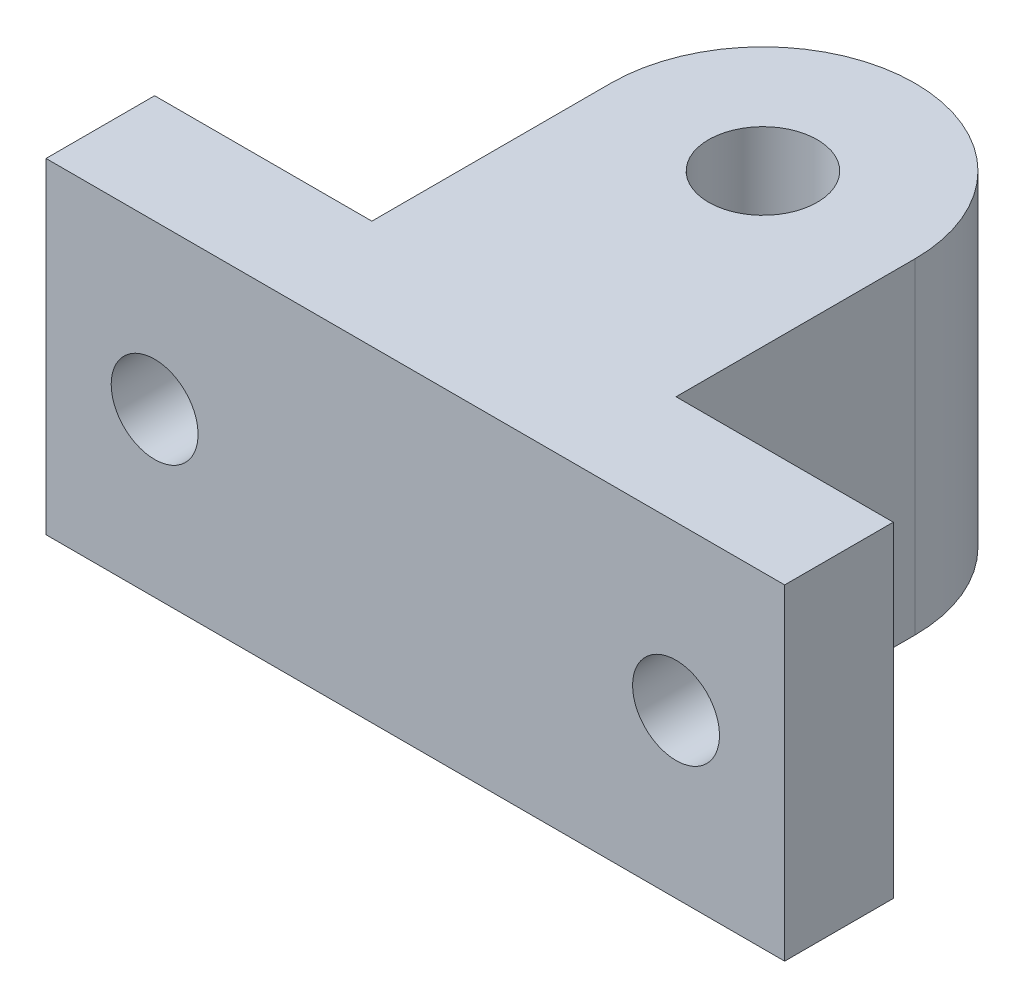
SolidWorks part; units mm, degrees
ref_plane "Plan de face" through (0, 0, 0) normal (0, 0, 1) x (1, 0, 0)
ref_plane "Plan de dessus" through (0, 0, 0) normal (0, 1, 0) x (1, 0, 0)
ref_plane "Plan de droite" through (0, 0, 0) normal (1, 0, 0) x (0, 0, -1)
sketch "Esquisse1" plane through (0, 0, 0) normal (0, 1, 0) x (1, 0, 0)
  line L0 (-7, 0) -> (-7, -11)
  line L1 (-7, -11) -> (-17, -11)
  line L2 (-17, -11) -> (-17, -16)
  line L3 (-17, -16) -> (17, -16)
  line L4 (17, -16) -> (17, -11)
  line L5 (7, 0) -> (7, -11)
  line L6 (7, -11) -> (17, -11)
  circle A0 centre (0, 0) radius 2.5
  arc A1 (7, 0) -> (-7, 0) centre (0, 0) ccw
  dimension "D1" = 5
  dimension "D2" = 7
  dimension "D3" = 16
  dimension "D4" = 5
  dimension "D5" = 10
extrude "Boss.-Extru.1" add sketch "Esquisse1" along normal blind 15
sketch "Esquisse2" plane through (0, 0, 11) normal (0, 0, -1) x (-1, 0, 0)
  line L0 (17, 15) -> (17, 0) construction
  line L1 (7, 15) -> (17, 15) construction
  circle A0 centre (12, 7.5) radius 2
  dimension "D1" = 4
  dimension "D2" = 5
  dimension "D3" = 7.5
extrude "Enlèv. mat.-Extru.1" cut sketch "Esquisse2" against normal blind 15
mirror "Symétrie1" about plane through (0, 0, 0) normal (1, 0, 0) of "Enlèv. mat.-Extru.1"
